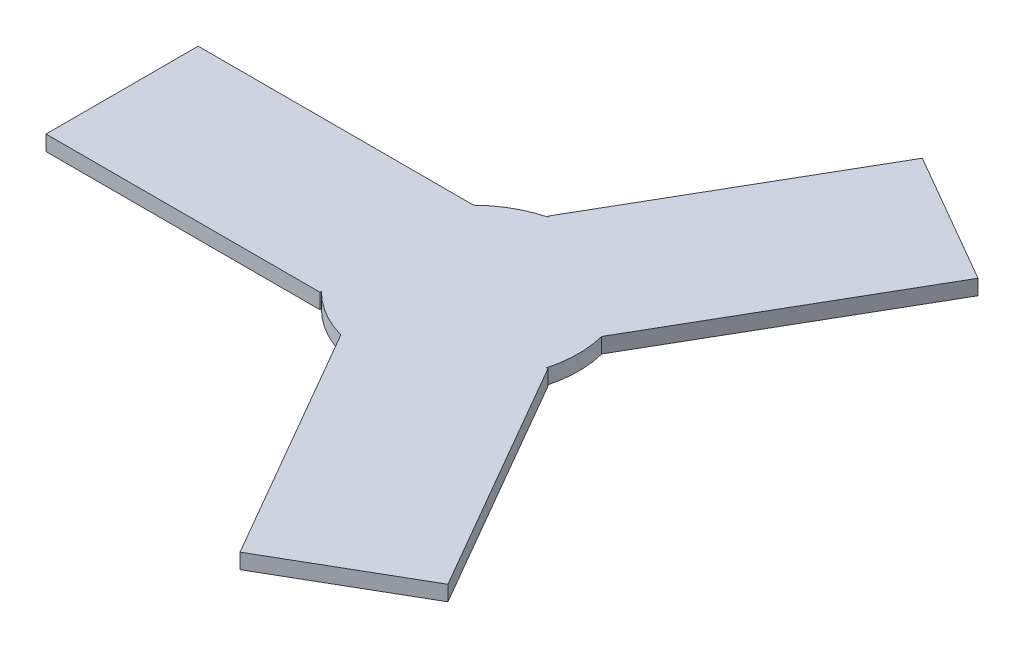
SolidWorks part; units mm, degrees
ref_plane "Plan de face" through (0, 0, 0) normal (0, 0, 1) x (1, 0, 0)
ref_plane "Plan de dessus" through (0, 0, 0) normal (0, 1, 0) x (1, 0, 0)
ref_plane "Plan de droite" through (0, 0, 0) normal (1, 0, 0) x (0, 0, -1)
sketch "Esquisse3" plane through (0, 0, 0) normal (0, 1, 0) x (1, 0, 0)
  line L0 (-150.1573, 0) -> (189.6273, 0) construction
  line L1 (-83.8395, -145.9242) -> (87.7229, 151.2306) construction
  line L2 (-78.0725, 135.2255) -> (117.7517, -203.9519) construction
  line L3 (-125, 131.2995) -> (-125, -153.5705) construction
  line L4 (-25, -25) -> (-115, -25)
  line L6 (-25, 25) -> (-24.4949, 25)
  line L7 (-115, -25) -> (-115, 25)
  line L8 (-25, -25) -> (-115, 25) construction
  line L9 (-25, 25) -> (-115, -25) construction
  line L10 (-24.4949, 25) -> (-115, 25)
  line L11 (33.8981, 8.7132) -> (79.1506, 87.0929)
  line L12 (35.8494, 112.0929) -> (79.1506, 87.0929)
  line L13 (-9.1506, 34.1506) -> (35.8494, 112.0929)
  line L14 (-9.4032, -33.7132) -> (35.8494, -112.0929)
  line L15 (79.1506, -87.0929) -> (35.8494, -112.0929)
  line L16 (34.1506, -9.1506) -> (79.1506, -87.0929)
  line L17 (-24.4949, 25) -> (-25, -25)
  line L18 (-9.1506, 34.1506) -> (33.8981, 8.7132)
  line L19 (-9.4032, -33.7132) -> (34.1506, -9.1506)
  circle A0 centre (0, 0) radius 125
  circle A1 centre (0, 0) radius 35
  circle A2 centre (0, 0) radius 125
  circle A3 centre (0, 0) radius 125
  point P9 (-70, 0)
  point P32 (0, 0)
  dimension "D1" = 250
  dimension "D4" = 70
  dimension "D2" = 120
  dimension "D3" = 120
  dimension "D5" = 10
  dimension "D6" = 50
  dimension "D7" = 90
  dimension "D8" = 3
extrude "Boss.-Extru.3" add sketch "Esquisse3" along normal blind 5 contours A1 L6 L10 L7 L4 L17 | A1 L14 L15 L16 L19 | L19 A1 L18 L17 | A1 L11 L12 L13 L18 | L18 A1
